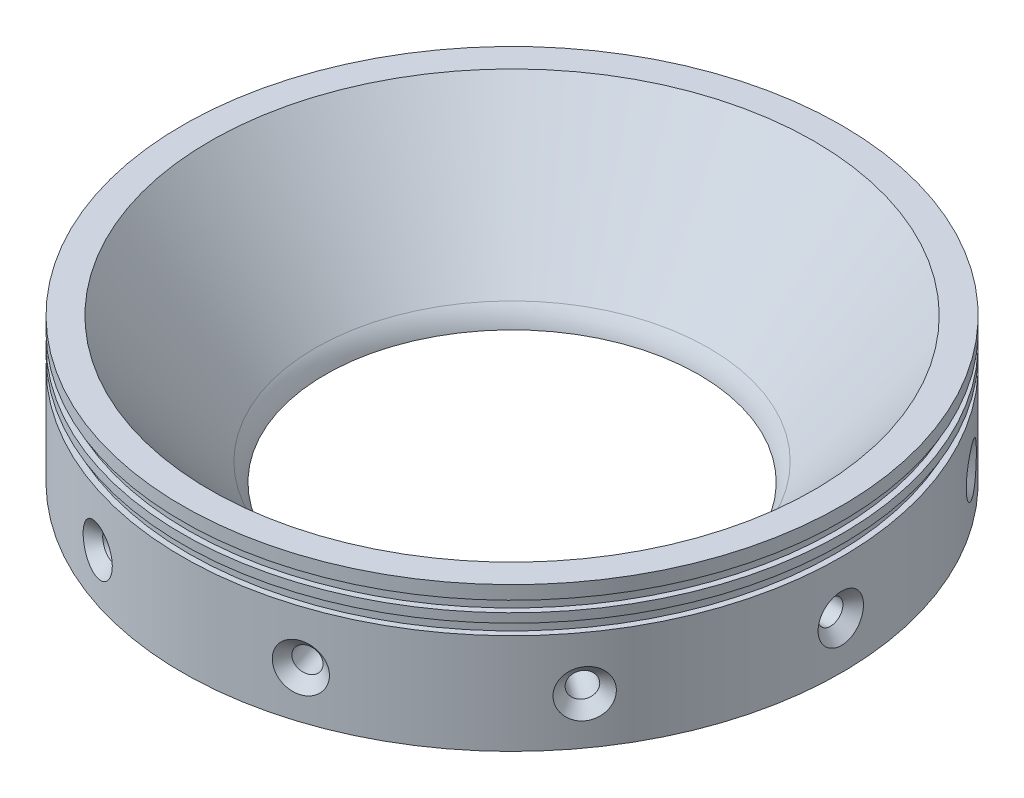
SolidWorks part; units mm, degrees
material "6061-T6 (SS)"
ref_plane "Piano frontale" through (0, 0, 0) normal (0, 0, 1) x (1, 0, 0)
ref_plane "Piano superiore" through (0, 0, 0) normal (0, 1, 0) x (1, 0, 0)
ref_plane "Piano destro" through (0, 0, 0) normal (1, 0, 0) x (0, 0, -1)
sketch "Schizzo1" plane through (0, 0, 0) normal (0, 0, 1) x (1, 0, 0)
  line L1 (-66.9051, 94.6405) -> (-43.5718, 66.6405)
  line L12 (-73, 91.6405) -> (-71.7, 91.6405)
  line L13 (-71.7, 91.6405) -> (-71.7, 89.2405)
  line L17 (-43.5718, 66.6405) -> (-73, 66.6405)
  line L18 (-73, 94.6405) -> (73, 94.6405) construction
  line L19 (-66.9051, 94.6405) -> (-73, 94.6405)
  line L20 (-73, 94.6405) -> (-73, 66.6405)
  line L22 (-73, 66.6405) -> (-73, 62.6405)
  line L24 (0, 0) -> (0, 138.6223) construction
  line L25 (-71.7, 89.2405) -> (-73, 89.2405)
  line L26 (-73, 87.2405) -> (-71.7, 87.2405)
  line L27 (-71.7, 87.2405) -> (-71.7, 84.8405)
  line L28 (-71.7, 84.8405) -> (-73, 84.8405)
  line L29 (-41, 63.5544) -> (-66.9051, 94.6405) construction
  line L33 (-73, 464.6405) -> (-73, 56.6405) construction
  line L34 (-73, 62.6405) -> (-41.3733, 62.6405)
  line L38 (-38, 64.6405) -> (-63, 94.6405)
  line L39 (-38, 42.2918) -> (-38, 64.6405)
  line L40 (-41, 42.2918) -> (-38, 42.2918)
  line L41 (-41, 63.5544) -> (-41, 42.2918)
  line L42 (-66.9051, 94.6405) -> (-41, 63.5544)
  line L43 (-63, 94.6405) -> (-66.9051, 94.6405)
  line L47 (-41, 59.9339) -> (-41, 42.2918)
  line L48 (-66.9051, 94.6405) -> (-43.3178, 66.3357)
  arc A0 (-41, 59.9339) -> (-43.5824, 66.6405) centre (-51, 59.9339) ccw
  dimension "D1" = 146
  dimension "D2" = 0
  dimension "D3" = 28
  dimension "D4" = 1.3
  dimension "D5" = 2.4
  dimension "D6" = 2
  dimension "D7" = 3
  dimension "D8" = 4
revolve "Rivoluzione1" add sketch "Schizzo1" angle 360 about L24
sketch "Schizzo2" [suppressed] plane through (0, 0, 0) normal (0, 0, 1) x (1, 0, 0)
  line L0 (-36, 69.6405) -> (-36, 79.6405)
  line L1 (-36, 79.6405) -> (-27.1326, 69.6405)
  line L2 (-27.1326, 69.6405) -> (-36, 69.6405)
  line L3 (0, 0) -> (0, 148.9745) construction
revolve "Taglia-Rivoluzione1" [suppressed] cut sketch "Schizzo2" angle 360 about L3
hole_wizard "Foro svasato per Vite M5-1" positions "Schizzo3D1" profile "Schizzo5" countersink size "M5" standard "ISO"
sketch3d "Schizzo3D1"
  line L0 (-73, 94.6405, 0) -> (-73, 66.6405, 0) construction
  point P0 (-73, 72.7995, 0)
  point P4 (-73, 72.7995, 0)
  point P6 (-73, 72.7995, 0)
  point P8 (-73, 72.3644, 0)
  point P10 (-73, 72.7995, 0)
  point P13 (-73, 73.0826, -0.0192)
sketch "Schizzo5" plane through (-73, 73.0826, -0.0192) normal (0, 1, 0) x (-0.0003, 0, 1)
  line L0 (0, 0) -> (0, 18)
  line L1 (0, 18) -> (2.75, 16.3476)
  line L2 (2.75, 16.3476) -> (2.75, 2.45)
  line L3 (2.75, 2.45) -> (5.2, 0)
  line L5 (5.2, 0) -> (0, 0)
  line L6 (-2.75, 2.45) -> (-5.2, 0) construction
  line L10 (0, 18) -> (-2.75, 16.3476) construction
  line L11 (0, -6.35) -> (0, 107.95) construction
  dimension "Hole Dia." = 5.5
  dimension "Hole Depth" = 18
  dimension "Near C'Sink Dia." = 10.4
  dimension "Near C'Sink Angle" = 90
  dimension "Drill Angle" = 118
pattern_circular "RipetizioneCircolare1" count 10 over 360 about axis through (0, 0, 0) along (0, -1, 0) of "Foro svasato per Vite M5-1"
